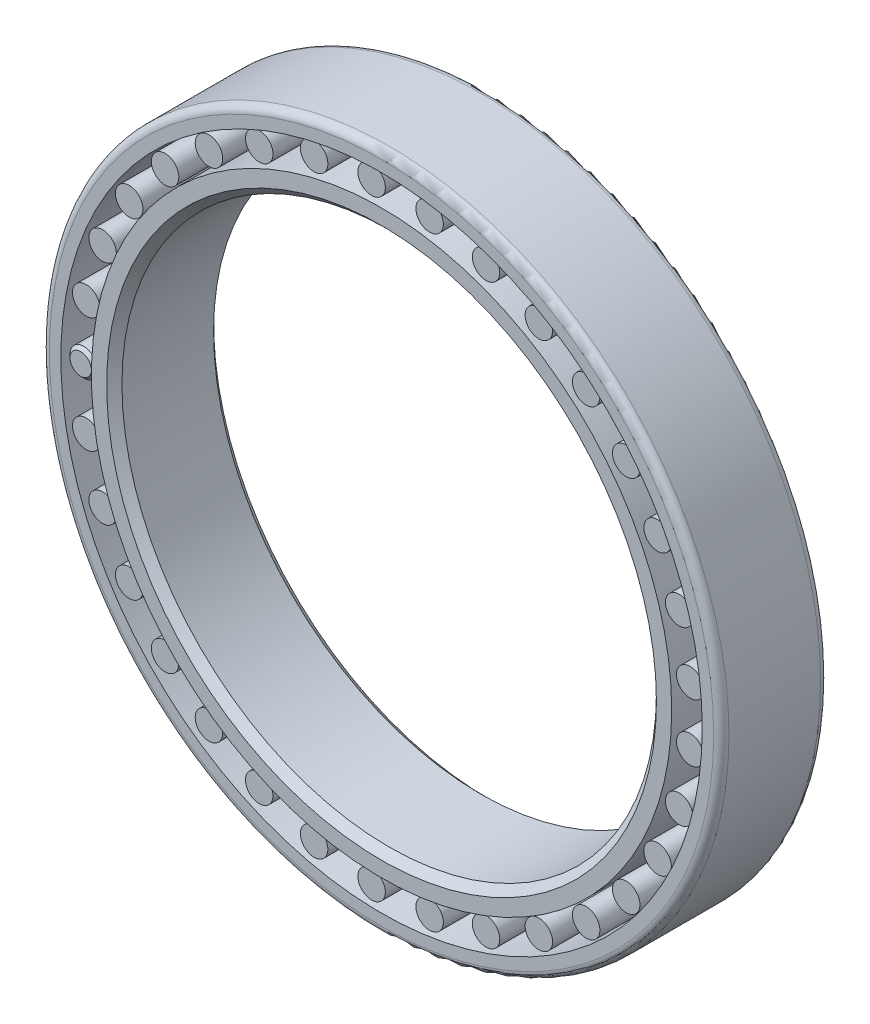
SolidWorks part; units mm, degrees
ref_plane "Plan de face" through (0, 0, 0) normal (0, 0, 1) x (1, 0, 0)
ref_plane "Plan de dessus" through (0, 0, 0) normal (0, 1, 0) x (1, 0, 0)
ref_plane "Plan de droite" through (0, 0, 0) normal (1, 0, 0) x (0, 0, -1)
sketch "Esquisse1" plane through (0, 0, 0) normal (0, 0, 1) x (1, 0, 0)
  circle A0 centre (0, 0) radius 22.25
  circle A1 centre (0, 0) radius 17.5
  dimension "D1" = 44.5
  dimension "D2" = 35
extrude "Boss.-Extru.1" add sketch "Esquisse1" along normal blind 7
sketch "Esquisse2" plane through (0, 0, 0) normal (0, 1, 0) x (1, 0, 0)
  line L0 (0, 0) -> (0, -14.157) construction
  line L1 (-21, 0.7917) -> (-21, -8.9987)
  line L2 (-21, -8.9987) -> (-19, -8.9987)
  line L3 (-19, -8.9987) -> (-19, 0.7917)
  line L4 (-19, 0.7917) -> (-21, 0.7917)
  dimension "D1" = 38
  dimension "D2" = 42
revolve "Enlèvement de matière-Révolution1" cut sketch "Esquisse2" angle 360 about L0
sketch "Esquisse3" plane through (0, 0, 0) normal (0, 1, 0) x (1, 0, 0)
  line L0 (-20, -8.5249) -> (-20, 1.8971) construction
  line L1 (0, 0) -> (0, -12.6832) construction
  line L2 (-20, -0.3) -> (-20.9, -0.3)
  line L3 (-20.9, -0.3) -> (-20.9, -6.7)
  line L4 (-20.9, -6.7) -> (-20, -6.7)
  line L5 (-20, -0.3) -> (-20, -6.7)
  line L6 (21, 0) -> (-21, 0) construction
  line L7 (-21, -7) -> (21, -7) construction
  dimension "D1" = 20
  dimension "D2" = 1.8
  dimension "D3" = 0.3
  dimension "D4" = 0.3
revolve "Révolution1" add sketch "Esquisse3" angle 360 about L0
pattern_circular "Répétition circulaire1" count 33 over 360 about axis through (0, 0, 0) along (0, 0, 1) of bodies 104
fillet "Congé1" radius 0.5 2 edges at (22.25, 0, 0) (22.25, 0, 7)
chamfer "Chanfrein1" distance 0.5 angle 45 2 edges at (17.5, 0, 0) (17.5, 0, 7)
chamfer "Chanfrein2" distance 0.2 angle 45 2 edges at (-19.1, 0, 0.3) (-19.1, 0, 6.7)
